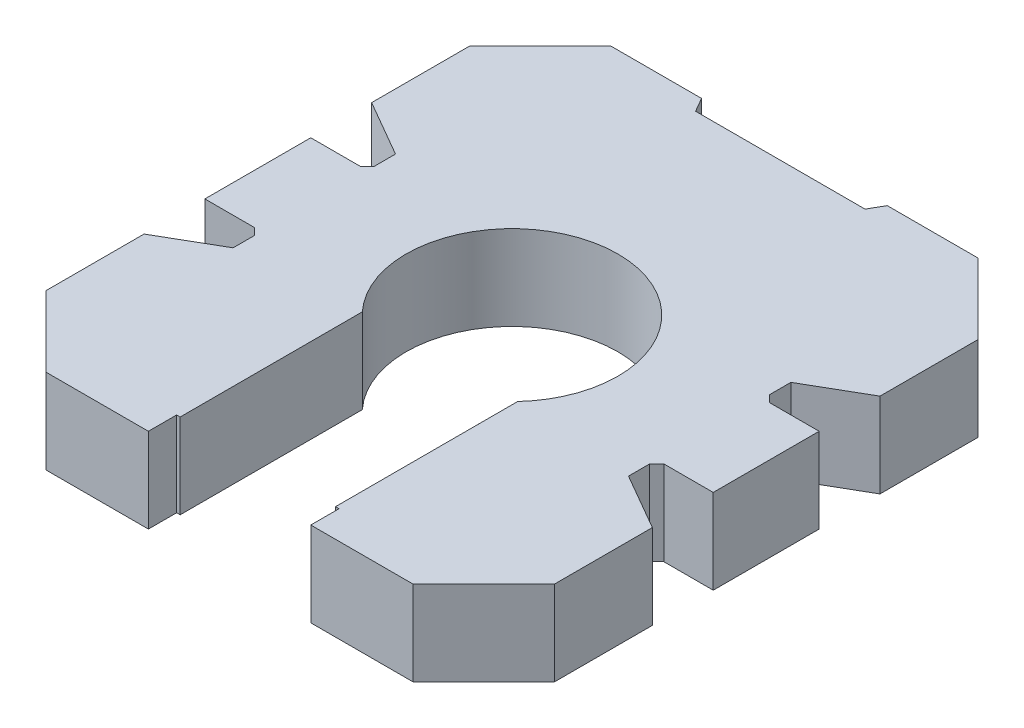
SolidWorks part; units mm, degrees
ref_plane "前视基准面" through (0, 0, 0) normal (0, 0, 1) x (1, 0, 0)
ref_plane "上视基准面" through (0, 0, 0) normal (0, 1, 0) x (1, 0, 0)
ref_plane "右视基准面" through (0, 0, 0) normal (1, 0, 0) x (0, 0, -1)
sketch "草图1" plane through (0, 0, 0) normal (0, 1, 0) x (1, 0, 0)
  line L1 (-180, 200) -> (180, 200)
  line L2 (-180, 200) -> (-180, -200)
  line L3 (-180, -200) -> (180, -200)
  line L4 (180, 200) -> (180, -200)
  line L5 (0, -200) -> (0, 200) construction
  line L6 (-180, 0) -> (180, 0) construction
  point P0 (0, 0)
  dimension "D1" = 400
  dimension "D2" = 360
extrude "凸台-拉伸1" add sketch "草图1" along normal blind 60
chamfer "倒角1" distance 50 angle 45 4 edges at (-180, 30, -200) (180, 30, -200) (-180, 30, 200) (180, 30, 200)
sketch "草图2" plane through (0, 60, 0) normal (0, 1, 0) x (1, 0, 0)
  line L0 (0, 148.814) -> (0, -134.4705) construction
  line L1 (-130.3803, 0) -> (-243.5683, 0) construction
  line L2 (-180, -57.5) -> (-180, 57.5)
  line L3 (-180, 150) -> (-180, -150) construction
  line L4 (-180, 57.5) -> (-140, 57.5)
  line L5 (-140, 57.5) -> (-140, -57.5)
  line L7 (-180, -57.5) -> (-140, -57.5)
  line L8 (180, -57.5) -> (140, -57.5)
  line L9 (140, 57.5) -> (140, -57.5)
  line L10 (180, 57.5) -> (140, 57.5)
  line L11 (180, -57.5) -> (180, 57.5)
  point P5 (180, 0)
  point P12 (-140, 0)
  point P13 (-180, 0)
  point P14 (140, 0)
  dimension "D1" = 40
  dimension "D2" = 115
extrude "切除-拉伸1" cut sketch "草图2" against normal through all
sketch "草图3" plane through (0, 60, 0) normal (0, 1, 0) x (1, 0, 0)
  line L0 (-140, -57.5) -> (-180, -57.5)
  line L1 (-180, -57.5) -> (-140, -57.5) construction
  line L2 (-180, -57.5) -> (-180, -80.594)
  line L3 (-180, -57.5) -> (-180, -150) construction
  line L4 (-180, -80.594) -> (-140, -57.5)
  line L5 (-204.8094, 0) -> (-103.8717, 0) construction
  line L6 (-180, 80.594) -> (-140, 57.5)
  line L7 (-180, 57.5) -> (-180, 80.594)
  line L8 (-140, 57.5) -> (-180, 57.5)
  line L9 (0, 86.5411) -> (0, -78.3789) construction
  line L10 (140, 57.5) -> (180, 57.5)
  line L11 (180, 57.5) -> (180, 80.594)
  line L12 (180, 80.594) -> (140, 57.5)
  line L13 (180, -80.594) -> (140, -57.5)
  line L14 (180, -57.5) -> (180, -80.594)
  line L15 (140, -57.5) -> (180, -57.5)
  point P22 (-140, -57.5)
  dimension "D1" = 120
extrude "切除-拉伸2" cut sketch "草图3" against normal blind 60
sketch "草图4" plane through (0, 0, 0) normal (0, 1, 0) x (1, 0, 0)
  line L0 (0, -218.4272) -> (0, 0) construction
  line L1 (-130, -200) -> (130, -200) construction
  line L2 (-55, -85) -> (55, -85)
  line L3 (-55, -85) -> (-55, -200)
  line L4 (-55, -200) -> (55, -200)
  line L5 (55, -85) -> (55, -200)
  line L6 (0, -200) -> (0, -85) construction
  line L7 (-55, -142.5) -> (55, -142.5) construction
  line L8 (-130, -200) -> (130, -200) construction
  line L9 (57.5, -180) -> (-57.5, -180)
  line L10 (57.5, -180) -> (57.5, -200)
  line L11 (57.5, -200) -> (-57.5, -200)
  line L12 (-57.5, -180) -> (-57.5, -200)
  line L13 (0, -200) -> (0, -180) construction
  line L14 (57.5, -190) -> (-57.5, -190) construction
  point P3 (0, -142.5)
  point P9 (0, -190)
  line M30 (130, -200) -> (-130, -200)
  dimension "D1" = 110
  dimension "D2" = 115
  dimension "D3" = 20
  dimension "D4" = 115
extrude "切除-拉伸3" cut sketch "草图4" along normal through all contours L5 L9 L3 L2 | L9 L5 L3 M30 | L12 L9 L3 M30 | L9 L10 L5 M30
sketch "草图5" plane through (0, 60, 0) normal (0, 1, 0) x (1, 0, 0)
  line L0 (0, 61.129) -> (0, -49.8005) construction
  line L1 (-231.4682, 0) -> (-167.6351, 0) construction
  line L2 (-140, -57.5) -> (-140, 57.5) construction
  line L3 (-180, -37.5) -> (-140, -37.5)
  line L4 (-180, -37.5) -> (-180, 37.5)
  line L5 (-180, 37.5) -> (-140, 37.5)
  line L6 (-140, -37.5) -> (-140, 37.5)
  line L7 (-160, 37.5) -> (-160, -37.5) construction
  line L8 (-180, 0) -> (-140, 0) construction
  line L9 (180, 0) -> (140, 0) construction
  line L10 (160, 37.5) -> (160, -37.5) construction
  line L11 (140, -37.5) -> (140, 37.5)
  line L12 (180, 37.5) -> (140, 37.5)
  line L13 (180, -37.5) -> (180, 37.5)
  line L14 (180, -37.5) -> (140, -37.5)
  point P5 (-160, 0)
  point P22 (160, 0)
  dimension "D1" = 75
  dimension "D2" = 40
extrude "凸台-拉伸2" add sketch "草图5" against normal up to surface (60 mm away) up to face at (0, 0, 53.75)
sketch "草图6" plane through (0, 60, 0) normal (0, 1, 0) x (1, 0, 0)
  line L0 (0, 310.5372) -> (0, 75.3035) construction
  line L1 (-65.7735, 200) -> (-60, 190)
  line L2 (130, 200) -> (-130, 200) construction
  line L3 (-60, 190) -> (60, 190)
  line L4 (-65.7735, 200) -> (65.7735, 200)
  line L5 (65.7735, 200) -> (60, 190)
  point P10 (0, 200)
  point P11 (0, 190)
  dimension "D1" = 120
  dimension "D2" = 120
  dimension "D3" = 10
extrude "切除-拉伸4" cut sketch "草图6" against normal blind 60
sketch "草图7" plane through (0, 60, 0) normal (0, 1, 0) x (1, 0, 0)
  circle A0 centre (0, 0) radius 75
  dimension "D1" = 150
extrude "切除-拉伸5" cut sketch "草图7" against normal blind 60
sketch "草图8" plane through (0, 60, 0) normal (0, 1, 0) x (1, 0, 0)
  line L0 (-55, -85) -> (-55, -50.9902)
  line L1 (55, -85) -> (55, -50.9902)
  line L2 (-55, -85) -> (55, -85)
  circle A0 centre (0, 0) radius 75 construction
  arc A1 (-55, -50.9902) -> (55, -50.9902) centre (0, 0) ccw
extrude "切除-拉伸6" cut sketch "草图8" against normal blind 60
chamfer "倒角2" distance 5 angle 45 4 edges at (-140, 30, -37.5) (-140, 30, 37.5) (140, 30, -37.5) (140, 30, 37.5)
